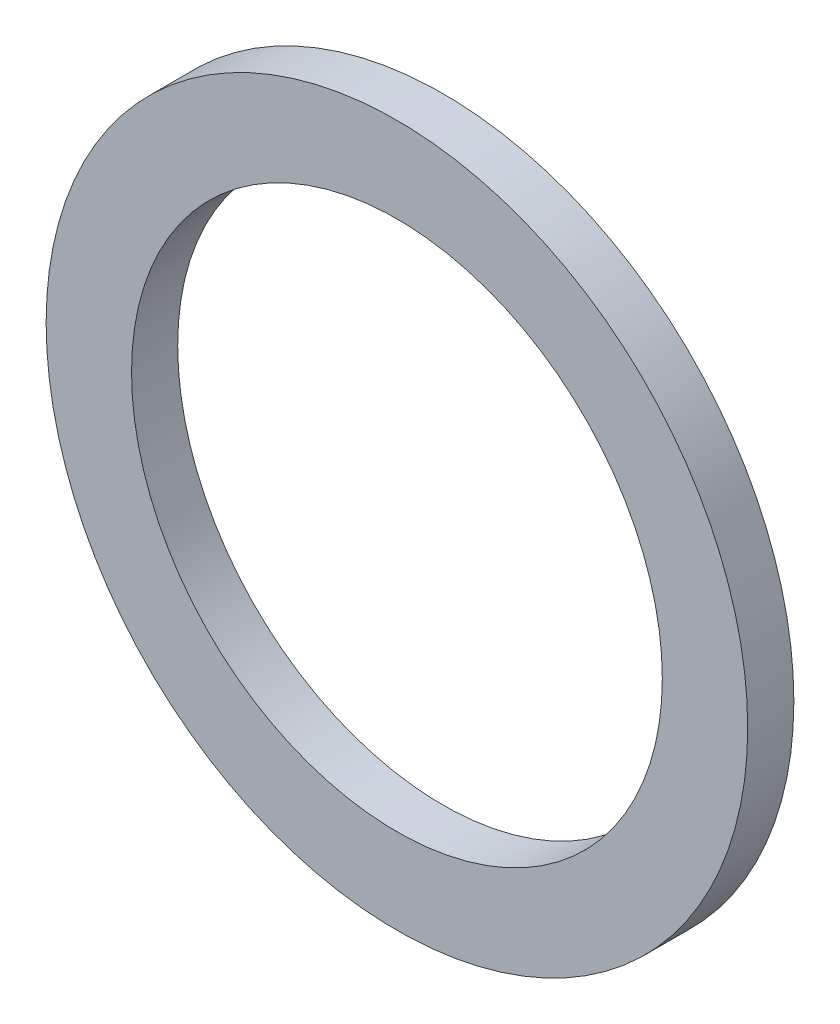
SolidWorks part; units mm, degrees
material "1.8159 (51CrV4)"
ref_plane "Front Plane" through (0, 0, 0) normal (0, 0, 1) x (1, 0, 0)
ref_plane "Top Plane" through (0, 0, 0) normal (0, 1, 0) x (1, 0, 0)
ref_plane "Right Plane" through (0, 0, 0) normal (1, 0, 0) x (0, 0, -1)
sketch "Sketch1" plane through (0, 0, 0) normal (0, 1, 0) x (1, 0, 0)
  line L0 (5.75, -45) -> (7.6, -45)
  line L1 (7.6, -45) -> (7.6, -46)
  line L2 (7.6, -46) -> (5.75, -46)
  line L3 (5.75, -46) -> (5.75, -45)
  line L4 (0, -150) -> (0, 150) construction
revolve "REV_DIN471_12x1_envelope" add sketch "Sketch1" angle 360 about L4
